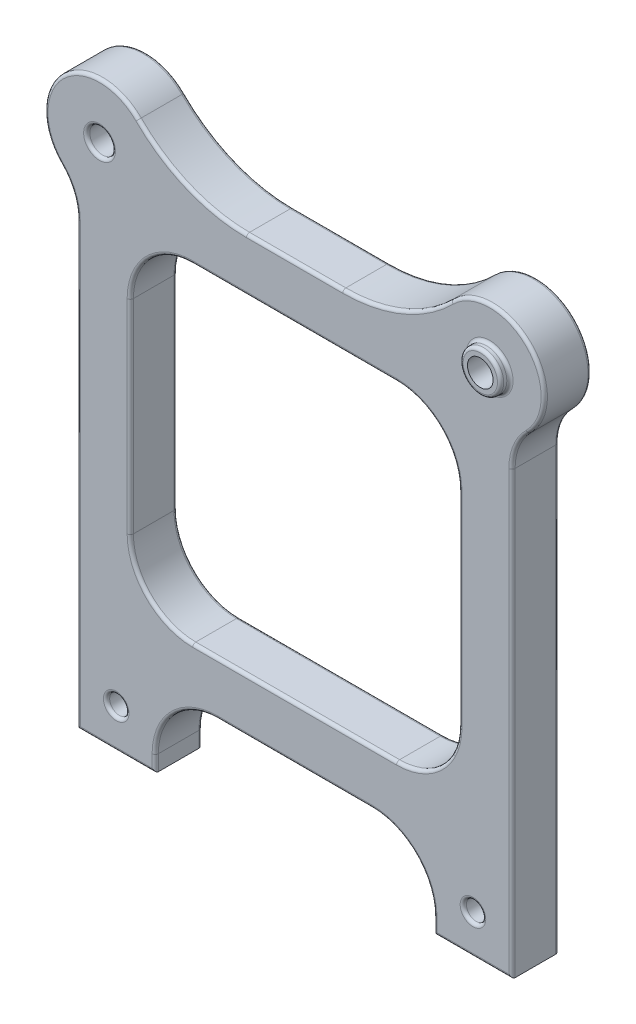
SolidWorks part; units mm, degrees
material "ABS"
ref_plane "Front Plane" through (0, 0, 0) normal (0, 0, 1) x (1, 0, 0)
ref_plane "Top Plane" through (0, 0, 0) normal (0, 1, 0) x (1, 0, 0)
ref_plane "Right Plane" through (0, 0, 0) normal (1, 0, 0) x (0, 0, -1)
sketch "Sketch1" plane through (0, 0, 0) normal (0, 0, 1) x (1, 0, 0)
  line L1 (-52.65, -52.65) -> (52.65, -52.65)
  line L2 (-52.65, -52.65) -> (-52.65, 52.65)
  line L3 (-52.65, 52.65) -> (52.65, 52.65)
  line L4 (52.65, -52.65) -> (52.65, 52.65)
  line L5 (-52.65, -52.65) -> (52.65, 52.65) construction
  line L6 (-52.65, 52.65) -> (52.65, -52.65) construction
  line L7 (69.65, -69.65) -> (69.65, 46.6629)
  line L9 (-69.65, -69.65) -> (-69.65, 46.6629)
  line L10 (-57.15, -82.15) -> (-57.15, -61.1097) construction
  line L12 (69.65, -69.65) -> (69.65, -94.65)
  line L13 (69.65, -94.65) -> (-69.65, -94.65)
  line L14 (-69.65, -69.65) -> (-69.65, -94.65)
  line L15 (-69.65, -69.65) -> (69.65, -69.65) construction
  line L16 (-69.65, 69.65) -> (69.65, 69.65) construction
  line L17 (69.65, -69.65) -> (69.65, 69.65) construction
  line L18 (0, 0) -> (0, 34.1364) construction
  line L19 (44.65, -94.65) -> (-44.65, -94.65)
  line L20 (-69.65, -69.65) -> (-69.65, 69.65) construction
  line L21 (-15.4228, 69.65) -> (15.4228, 69.65)
  line L22 (-62.5, 71.65) -> (62.5, 71.65) construction
  line L23 (50.1256, 84.0244) -> (74.8744, 59.2756) construction
  line L24 (44.65, -94.65) -> (44.65, -69.65)
  line L25 (44.65, -69.65) -> (-44.65, -69.65)
  line L26 (-44.65, -94.65) -> (-44.65, -69.65)
  circle A9 centre (-62.5, 71.65) radius 4.1
  circle A10 centre (62.5, 71.65) radius 4.1
  arc A11 (50.1256, 84.0244) -> (74.8744, 59.2756) centre (62.5, 71.65) cw
  arc A12 (74.8744, 59.2756) -> (69.65, 46.6629) centre (87.4871, 46.6629) ccw
  arc A13 (15.4228, 69.65) -> (50.1256, 84.0244) centre (15.4228, 118.7272) ccw
  arc A14 (-74.8744, 59.2756) -> (-69.65, 46.6629) centre (-87.4871, 46.6629) cw
  arc A15 (-50.1256, 84.0244) -> (-74.8744, 59.2756) centre (-62.5, 71.65) ccw
  arc A16 (-15.4228, 69.65) -> (-50.1256, 84.0244) centre (-15.4228, 118.7272) cw
  circle A17 centre (-57.15, -82.15) radius 3.1
  circle A19 centre (57.15, -82.15) radius 3.1
  point P0 (0, 0)
  dimension "D8" = 8.2
  dimension "D4" = 17.5
  dimension "D12" = 6.2
  dimension "D1" = 105.3
  dimension "D3" = 42
  dimension "D7" = 17
  dimension "D6" = 125
  dimension "D5" = 2
  dimension "D9" = 45
  dimension "D10" = 17
  dimension "D11" = 25
  dimension "D13" = 12.5
  dimension "D2" = 17
extrude "Boss-Extrude2" add sketch "Sketch1" along normal blind 15
sketch "Sketch2" plane through (0, 0, 0) normal (0, 0, 1) x (1, 0, 0)
  line L0 (0, 0) -> (0, -42.2235) construction
  line L1 (69.65, -94.65) -> (44.65, -94.65) construction
  circle A0 centre (35, -87.15) radius 3
  circle A1 centre (-35, -87.15) radius 3
  dimension "D1" = 6
  dimension "D2" = 7.5
  dimension "D3" = 35
extrude "Cut-Extrude1" [suppressed] cut sketch "Sketch2" along normal up to surface (15 mm away)
fillet "Fillet3" radius 20 4 edges at (52.65, 52.65, 7.5) (52.65, -52.65, 7.5) (-52.65, -52.65, 7.5) (-52.65, 52.65, 7.5)
fillet "Fillet5" radius 20 2 edges at (-44.65, -69.65, 7.5) (44.65, -69.65, 7.5)
sketch "Sketch6" plane through (0, 0, 0) normal (0, 0, -1) x (-1, 0, 0)
  circle A0 centre (-62.5, 71.65) radius 6.5
  circle A7 centre (-62.5, 71.65) radius 4.1 construction
  circle A9 centre (-62.5, 71.65) radius 4.1
  dimension "D1" = 13
extrude "Boss-Extrude5" [suppressed] add sketch "Sketch6" along normal blind 3
ref_plane "Mid_Plane" through (0, 0, 7.5) normal (0, 0, 1) x (1, 0, 0)
sketch "Sketch7" plane through (0, 0, 15) normal (0, 0, 1) x (1, 0, 0)
  circle A0 centre (-62.5, 71.65) radius 4.1 construction
  circle A1 centre (-62.5, 71.65) radius 4.1
  circle A2 centre (-62.5, 71.65) radius 6.5
  dimension "D1" = 13
extrude "Boss-Extrude6" [suppressed] add sketch "Sketch7" along normal blind 3
sketch "Sketch8" plane through (0, 0, 15) normal (0, 0, 1) x (1, 0, 0)
  circle A0 centre (62.5, 71.65) radius 4.1 construction
  circle A1 centre (62.5, 71.65) radius 4.1
  circle A2 centre (62.5, 71.65) radius 6.5
  dimension "D1" = 13
extrude "Boss-Extrude7" add sketch "Sketch8" along normal blind 3
sketch "Sketch9" plane through (0, 0, 0) normal (0, 0, -1) x (-1, 0, 0)
  circle A0 centre (62.5, 71.65) radius 4.1 construction
  circle A1 centre (62.5, 71.65) radius 4.1
  circle A2 centre (62.5, 71.65) radius 6.5
  dimension "D1" = 13
extrude "Boss-Extrude8" add sketch "Sketch9" along normal blind 3
fillet "Fillet1" radius 1 56 edges at (0, 52.65, 15) (-52.65, 0, 15) (0, -52.65, 15) (52.65, 0, 15) (0, 69.65, 15) (69.65, -23.9936, 15) (-57.15, -94.65, 15) (57.15, -94.65, 15) (-69.65, -23.9936, 15) (66.6, 71.65, 0) (0, -52.65, 0) (-52.65, 0, 0) (0, 52.65, 0) (52.65, 0, 0) (-69.65, -23.9936, 0) (57.15, -94.65, 0) (-57.15, -94.65, 0) (69.65, -23.9936, 0) (0, 69.65, 0) (-58.4, 71.65, 15) (34.2039, 73.3858, 15) (74.8744, 84.0244, 15) (71.0078, 53.4889, 15) (-71.0078, 53.4889, 15) (-74.8744, 84.0244, 15) (-34.2039, 73.3858, 15) (-34.2039, 73.3858, 0) (-74.8744, 84.0244, 0) (-71.0078, 53.4889, 0) (71.0078, 53.4889, 0) (74.8744, 84.0244, 0) (34.2039, 73.3858, 0) (46.7921, 46.7921, 15) (-46.7921, 46.7921, 15) (-46.7921, -46.7921, 15) (46.7921, -46.7921, 15) (-46.7921, -46.7921, 0) (-46.7921, 46.7921, 0) (46.7921, 46.7921, 0) (46.7921, -46.7921, 0) (44.65, -92.15, 15) (0, -69.65, 15) (-44.65, -92.15, 15) (-44.65, -92.15, 0) (0, -69.65, 0) (44.65, -92.15, 0) (60.25, -82.15, 15) (-54.05, -82.15, 15) (60.25, -82.15, 0) (-54.05, -82.15, 0) (38.7921, -75.5079, 15) (-38.7921, -75.5079, 15) (-38.7921, -75.5079, 0) (38.7921, -75.5079, 0) (69, 71.65, 15) (-56, 71.65, 0)
fillet "Fillet6" radius 1 2 edges at (-69, 71.65, -3) (69, 71.65, 18)
fillet "Fillet7" [suppressed] radius 1
equation "\"D2@Sketch1\"=\"D7@Sketch1\""
